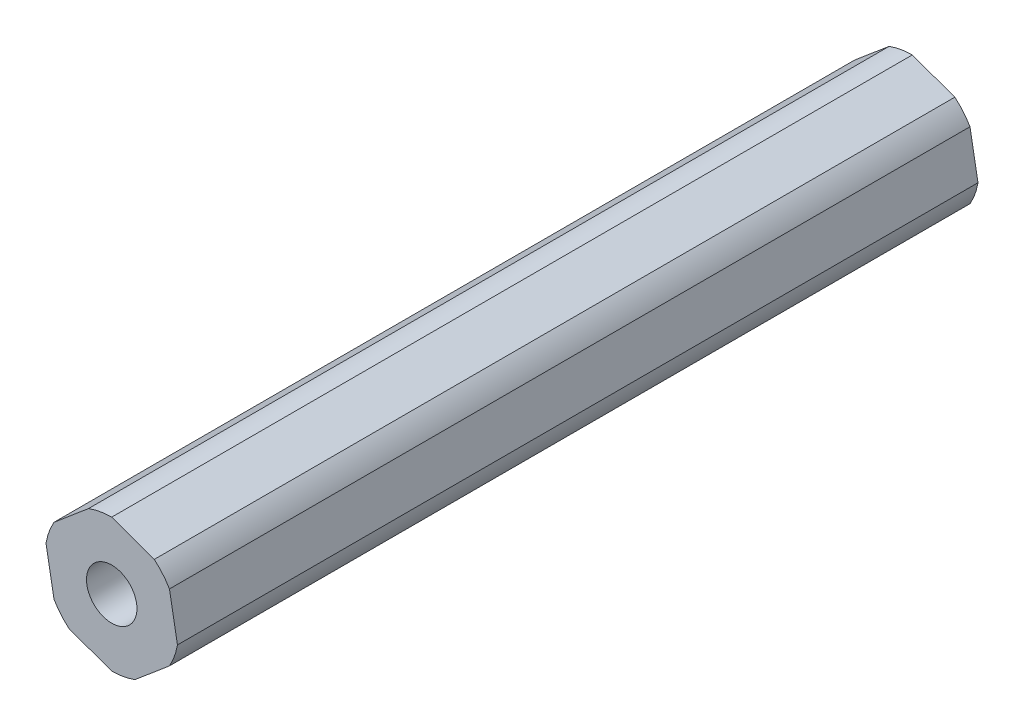
SolidWorks part; units mm, degrees
material "7075-T6 (SN)"
ref_plane "Front Plane" through (0, 0, 0) normal (0, 0, 1) x (1, 0, 0)
ref_plane "Top Plane" through (0, 0, 0) normal (0, 1, 0) x (1, 0, 0)
ref_plane "Right Plane" through (0, 0, 0) normal (1, 0, 0) x (0, 0, -1)
sketch "Sketch1" plane through (0, 0, 0) normal (0, 0, 1) x (1, 0, 0)
  line L1 (-6.6545, 1.1312) -> (-5.8457, -3.375)
  line L2 (-4.3069, -5.1974) -> (0, -6.75)
  line L3 (2.3476, -6.3286) -> (5.8457, -3.375)
  line L4 (6.6545, -1.1312) -> (5.8457, 3.375)
  line L5 (4.3069, 5.1974) -> (0, 6.75)
  line L6 (-2.3476, 6.3286) -> (-5.8457, 3.375)
  circle A0 centre (0, 0) radius 6.35 construction
  arc A1 (-5.8457, 3.375) -> (-6.6545, 1.1312) centre (0, 0) ccw
  arc A2 (-5.8457, -3.375) -> (-4.3069, -5.1974) centre (0, 0) ccw
  arc A3 (0, -6.75) -> (2.3476, -6.3286) centre (0, 0) ccw
  arc A4 (5.8457, -3.375) -> (6.6545, -1.1312) centre (0, 0) ccw
  arc A5 (5.8457, 3.375) -> (4.3069, 5.1974) centre (0, 0) ccw
  arc A6 (0, 6.75) -> (-2.3476, 6.3286) centre (0, 0) ccw
  dimension "D1" = 12.7
  dimension "D2" = 13.5
extrude "Boss-Extrude1" add sketch "Sketch1" along normal blind 81.0641
sketch "Sketch2" plane through (0, 0, 81.0641) normal (0, 0, 1) x (1, 0, 0)
  circle A0 centre (0, 0) radius 2.0193
  dimension "D1" = 4.0386
extrude "Cut-Extrude1" cut sketch "Sketch2" against normal through all
hole_wizard "1/4-20 Tapped Hole1" positions "Sketch5" profile "Sketch6" tap size "1/4-20" standard "ANSI Inch"
sketch "Sketch5" plane through (0, 0, 81.0641) normal (0, 0, 1) x (1, 0, 0)
  point P0 (0, 0)
sketch "Sketch6" plane through (0, 0, 81.0641) normal (1, 0, 0) x (0, -1, 0)
  line L0 (0, 0) -> (0, 20.5838)
  line L1 (0, 20.5838) -> (2.5527, 19.05)
  line L2 (2.5527, 19.05) -> (2.5527, 0)
  line L5 (2.5527, 0) -> (0, 0)
  line L10 (0, 20.5838) -> (-2.5527, 19.05) construction
  line L11 (0, -6.35) -> (0, 107.95) construction
  dimension "Tap Drill Dia." = 5.1054
  dimension "Tap Drill Depth" = 19.05
  dimension "Drill Angle" = 118
cosmetic thread "Hole Thread1" parameters "D1"=12.7, "D2"=6.35
hole_wizard "1/4-20 Tapped Hole2" positions "Sketch7" profile "Sketch8" tap size "1/4-20" standard "ANSI Inch"
sketch "Sketch7" plane through (0, 0, 0) normal (0, 0, -1) x (-1, 0, 0)
  point P0 (0, 0)
sketch "Sketch8" plane through (0, 0, 0) normal (1, 0, 0) x (0, 1, 0)
  line L0 (0, 0) -> (0, 20.5838)
  line L1 (0, 20.5838) -> (2.5527, 19.05)
  line L2 (2.5527, 19.05) -> (2.5527, 0)
  line L5 (2.5527, 0) -> (0, 0)
  line L10 (0, 20.5838) -> (-2.5527, 19.05) construction
  line L11 (0, -6.35) -> (0, 107.95) construction
  dimension "Tap Drill Dia." = 5.1054
  dimension "Tap Drill Depth" = 19.05
  dimension "Drill Angle" = 118
cosmetic thread "Hole Thread2" parameters "D1"=12.7, "D2"=6.35
